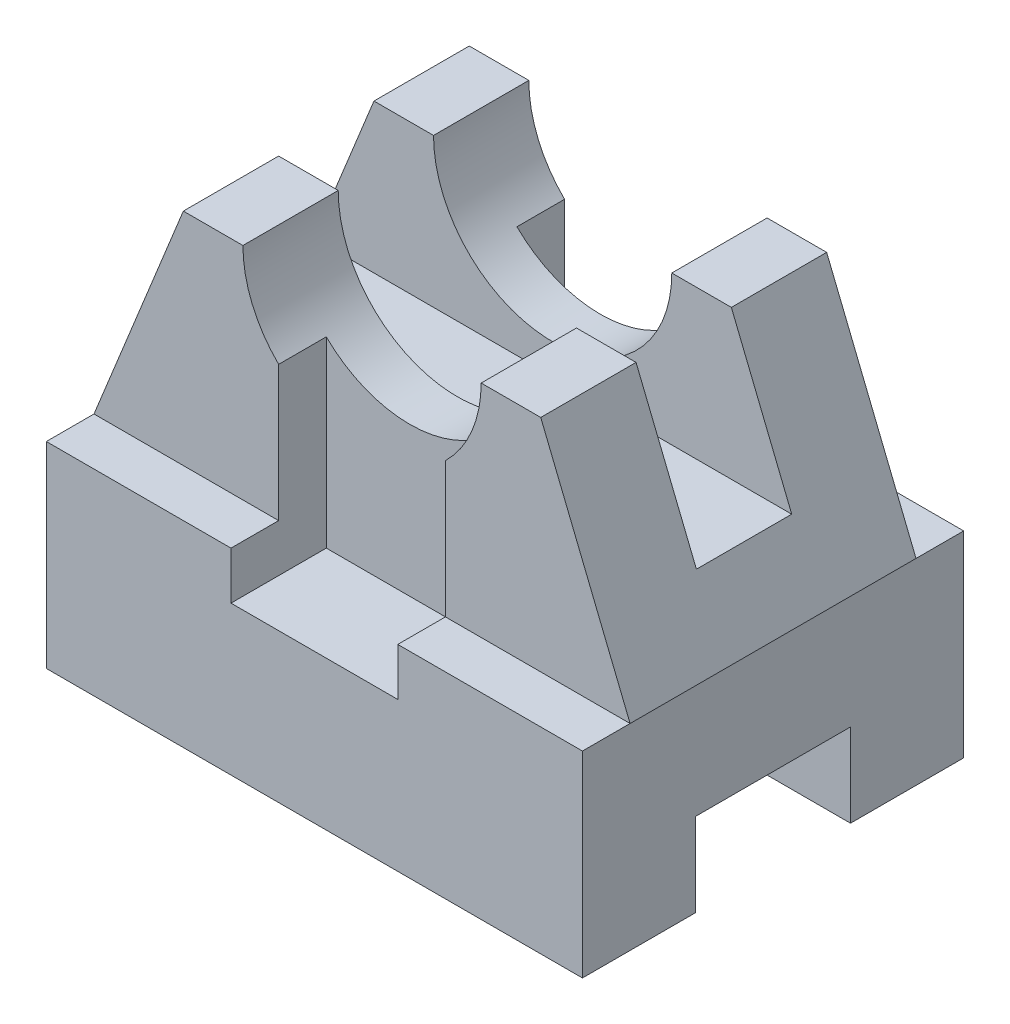
SolidWorks part; units mm, degrees
ref_plane "Front Plane" through (0, 0, 0) normal (0, 0, 1) x (1, 0, 0)
ref_plane "Top Plane" through (0, 0, 0) normal (0, 1, 0) x (1, 0, 0)
ref_plane "Right Plane" through (0, 0, 0) normal (1, 0, 0) x (0, 0, -1)
sketch "Sketch1" plane through (0, 0, 0) normal (0, 1, 0) x (1, 0, 0)
  line L1 (-45, 32) -> (45, 32)
  line L2 (-45, 32) -> (-45, -32)
  line L3 (-45, -32) -> (45, -32)
  line L4 (45, 32) -> (45, -32)
  line L5 (-45, 32) -> (45, -32) construction
  line L6 (-45, -32) -> (45, 32) construction
  point P0 (0, 0)
  dimension "D1" = 90
  dimension "D2" = 64
extrude "Boss-Extrude1" add sketch "Sketch1" along normal blind 33
sketch "Sketch2" plane through (0, 0, 0) normal (0, 0, 1) x (1, 0, 0)
  line L0 (45, 33) -> (-45, 33)
  line L1 (0, 0) -> (0, 70) construction
  line L2 (-45, 33) -> (-30, 70)
  line L3 (-30, 70) -> (-20, 70)
  line L4 (45, 33) -> (30, 70)
  line L5 (30, 70) -> (20, 70)
  arc A0 (-20, 70) -> (20, 70) centre (0, 70) ccw
  dimension "D1" = 40
  dimension "D2" = 70
  dimension "D3" = 10
extrude "Boss-Extrude2" add sketch "Sketch2" along normal blind 24 and the other way blind 24
sketch "Sketch3" plane through (0, 70, 0) normal (0, 1, 0) x (1, 0, 0)
  line L0 (45, 24) -> (45, -24) construction
  line L1 (-45, 8) -> (45, 8)
  line L2 (-45, 8) -> (-45, -8)
  line L3 (-45, -8) -> (45, -8)
  line L4 (45, 8) -> (45, -8)
  line L5 (-45, 8) -> (45, -8) construction
  line L6 (-45, -8) -> (45, 8) construction
  point P0 (0, 0)
  dimension "D1" = 16
extrude "Cut-Extrude1" cut sketch "Sketch3" against normal blind 25
sketch "Sketch4" plane through (0, 70, 0) normal (0, 1, 0) x (1, 0, 0)
  line L0 (0, 0) -> (0, 40.9592) construction
  line L2 (-14, 32) -> (14, 32)
  line L3 (-14, 32) -> (-14, 16)
  line L4 (-14, 16) -> (14, 16)
  line L5 (14, 32) -> (14, 16)
  line L6 (-14, 32) -> (14, 16) construction
  line L7 (-14, 16) -> (14, 32) construction
  line L8 (45, 32) -> (-45, 32) construction
  point P3 (0, 24)
  point P8 (0, 0)
  point P9 (0, 0)
  dimension "D1" = 28
  dimension "D2" = 16
extrude "Cut-Extrude2" cut sketch "Sketch4" against normal blind 45
mirror "Mirror1" about plane through (0, 0, 0) normal (0, 0, 1) of "Cut-Extrude2"
sketch "Sketch6" plane through (0, 0, 0) normal (0, -1, 0) x (1, 0, 0)
  line L0 (45, 32) -> (45, -32) construction
  line L1 (-45, 13) -> (45, 13)
  line L2 (-45, 13) -> (-45, -13)
  line L3 (-45, -13) -> (45, -13)
  line L4 (45, 13) -> (45, -13)
  line L5 (-45, 13) -> (45, -13) construction
  line L6 (-45, -13) -> (45, 13) construction
  point P0 (0, 0)
  dimension "D1" = 26
extrude "Cut-Extrude3" cut sketch "Sketch6" against normal blind 14
